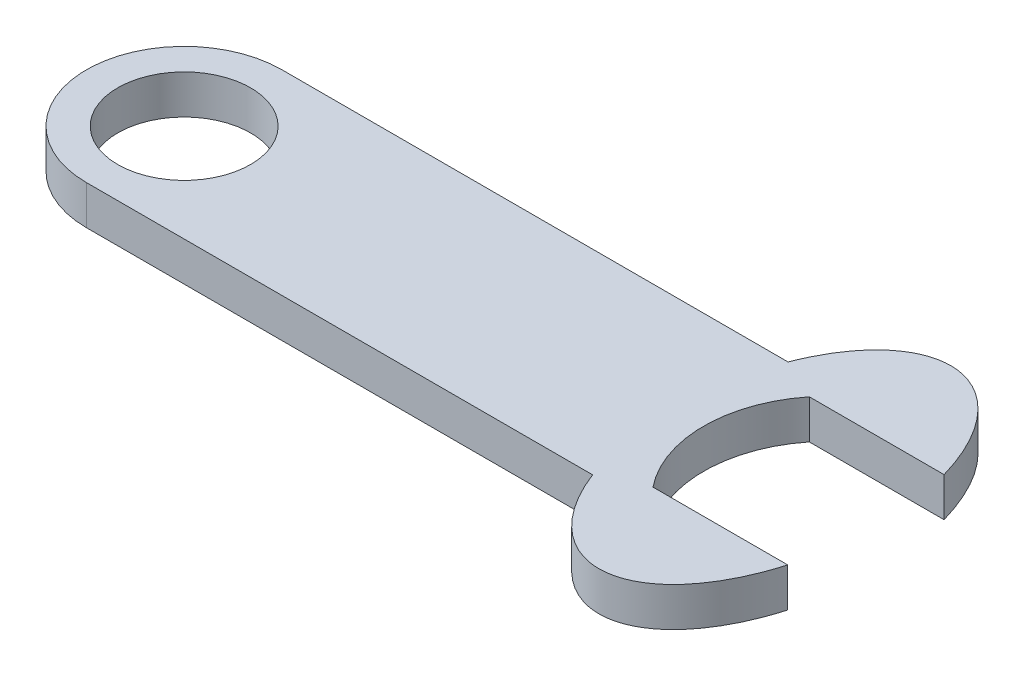
SolidWorks part; units mm, degrees
ref_plane "Front Plane" through (0, 0, 0) normal (0, 0, 1) x (1, 0, 0)
ref_plane "Top Plane" through (0, 0, 0) normal (0, 1, 0) x (1, 0, 0)
ref_plane "Right Plane" through (0, 0, 0) normal (1, 0, 0) x (0, 0, -1)
sketch "Sketch3" plane through (0, 0, 0) normal (0, 1, 0) x (1, 0, 0)
  line L0 (-151.1, 0) -> (-18.2, 0) construction
  line L3 (13.8, 79.0525) -> (13.8, -79.0525) construction
  line L4 (-151.1, 0) -> (13.8, 0) construction
  line L9 (-151.1, 25) -> (-21.6185, 25)
  line L10 (-151.1, -25) -> (-21.6185, -25)
  line L12 (-11.18, 20) -> (23.291, 20)
  line L13 (-11.18, -20) -> (23.291, -20)
  circle A2 centre (-151.1, 0) radius 17
  arc A3 (-151.1, 25) -> (-151.1, -25) centre (-151.1, 0) ccw
  arc A6 (-11.18, 20) -> (-11.18, -20) centre (13.8, 0) ccw
  ellipse E0 centre (0, 0) end of major axis (0, -45) minor radius 26 (23.291, 20) -> (-21.6185, 25) ccw
  ellipse E1 centre (0, 0) end of major axis (0, -45) minor radius 26 (-21.6185, -25) -> (23.291, -20) ccw
  point P3 (-43.5573, 0)
  point P4 (-68.65, 0)
  point P13 (13.8, 0)
  dimension "D6" = 90
  dimension "D2" = 34
  dimension "D3" = 13.8
  dimension "D8" = 64
  dimension "D1" = 25
  dimension "D4" = 164.9
  dimension "D7" = 26
  dimension "D10" = 20
  dimension "D11" = 40
extrude "Boss-Extrude1" add sketch "Sketch3" along normal blind 10
